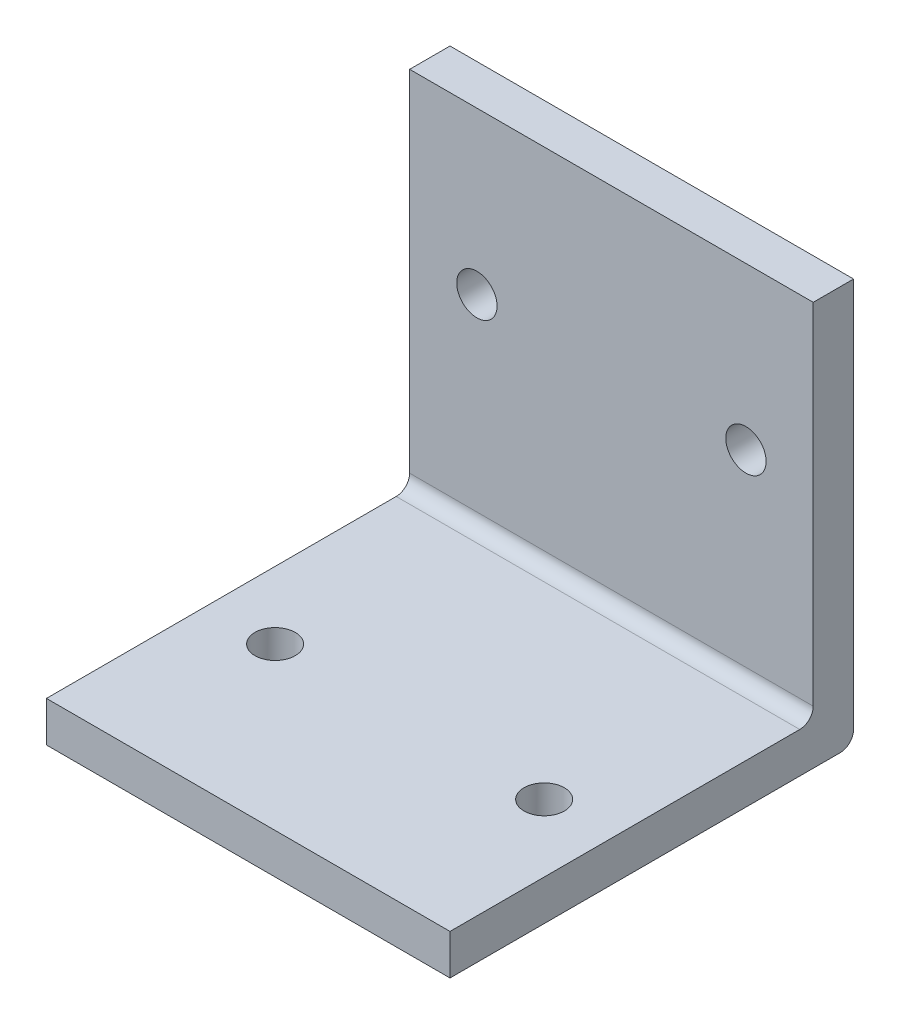
SolidWorks part; units mm, degrees
ref_plane "前视基准面" through (0, 0, 0) normal (0, 0, 1) x (1, 0, 0)
ref_plane "上视基准面" through (0, 0, 0) normal (0, 1, 0) x (1, 0, 0)
ref_plane "右视基准面" through (0, 0, 0) normal (1, 0, 0) x (0, 0, -1)
sketch "草图1" plane through (0, 0, 0) normal (0, 0, 1) x (1, 0, 0)
  line L1 (15, -15) -> (-15, -15)
  line L2 (15, -15) -> (15, 15)
  line L3 (15, 15) -> (-15, 15)
  line L4 (-15, -15) -> (-15, 15)
  line L5 (15, -15) -> (-15, 15) construction
  line L6 (15, 15) -> (-15, -15) construction
  point P0 (0, 0)
  dimension "D1" = 30
  dimension "D2" = 30
extrude "凸台-拉伸1" add sketch "草图1" along normal blind 3
sketch "草图2" plane through (0, 0, 3) normal (0, 0, 1) x (1, 0, 0)
  line L0 (0, -15) -> (0, 3) construction
  line L1 (-15, -15) -> (15, -15) construction
  circle A0 centre (10, 3) radius 1.5
  circle A1 centre (-10, 3) radius 1.5
  dimension "D2" = 10
  dimension "D3" = 3
  dimension "D5" = 3
  dimension "D1" = 18
  dimension "D4" = 10
extrude "切除-拉伸1" cut sketch "草图2" against normal blind 3.5
sketch "草图3" plane through (0, 0, 3) normal (0, 0, 1) x (1, 0, 0)
  line L0 (15, -15) -> (15, 15) construction
  line L1 (-15, -15) -> (15, -15)
  line L2 (-15, -15) -> (-15, -12)
  line L3 (-15, -12) -> (15, -12)
  line L4 (15, -15) -> (15, -12)
  dimension "D1" = 3
extrude "凸台-拉伸2" add sketch "草图3" along normal blind 27
sketch "草图4" plane through (0, -12, 0) normal (0, 1, 0) x (1, 0, 0)
  line L0 (0, -3) -> (0, -18)
  line L1 (15, -3) -> (-15, -3) construction
  circle A0 centre (-10, -18) radius 1.5
  circle A1 centre (10, -18) radius 1.5
  dimension "D2" = 10
  dimension "D4" = 3
  dimension "D5" = 3
  dimension "D1" = 15
  dimension "D3" = 10
extrude "切除-拉伸2" cut sketch "草图4" against normal blind 27 contours A1 | A0
fillet "圆角1" radius 1 1 edges at (0, -12, 3)
fillet "圆角2" radius 1 1 edges at (0, -15, 0)
